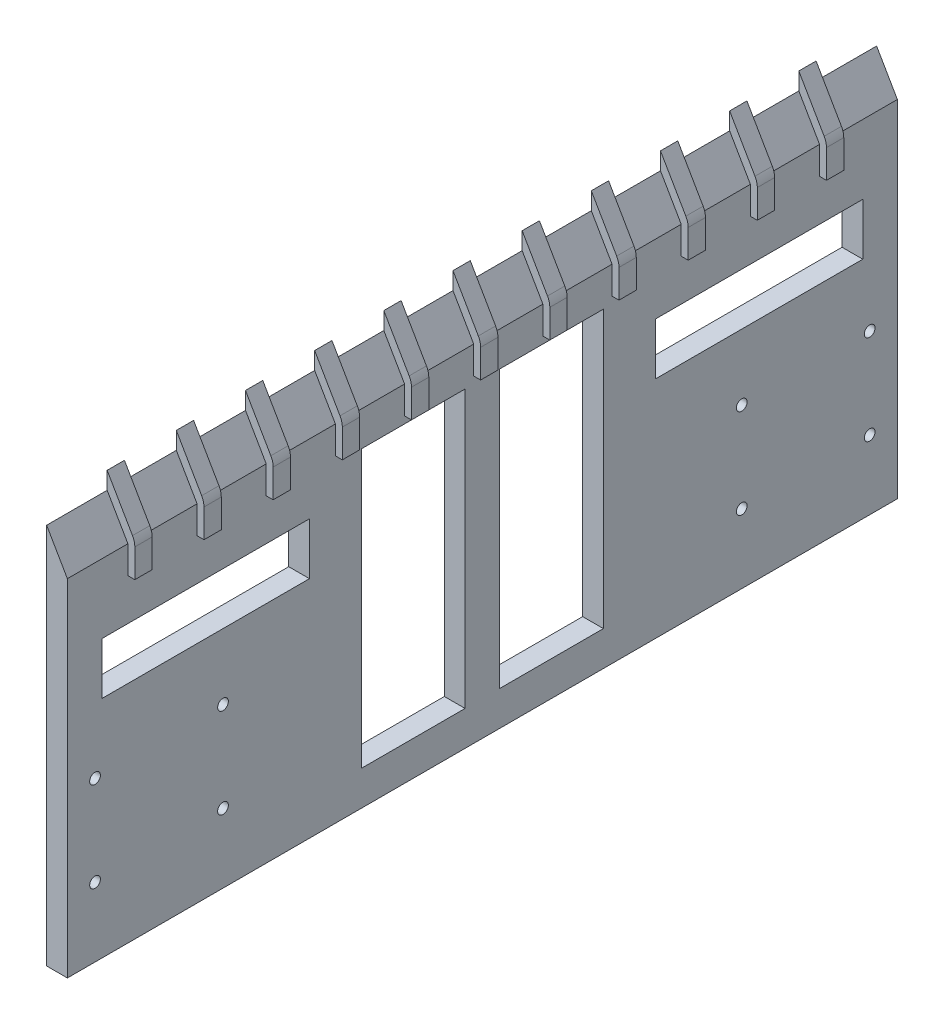
SolidWorks part; units mm, degrees
ref_plane "前视基准面" through (0, 0, 0) normal (0, 0, 1) x (1, 0, 0)
ref_plane "上视基准面" through (0, 0, 0) normal (0, 1, 0) x (1, 0, 0)
ref_plane "右视基准面" through (0, 0, 0) normal (1, 0, 0) x (0, 0, -1)
sketch "草图1" plane through (0, 0, 0) normal (1, 0, 0) x (0, 0, -1)
  line L1 (0, 0) -> (240, 0)
  line L2 (0, 0) -> (0, -100)
  line L3 (0, -100) -> (240, -100)
  line L4 (240, 0) -> (240, -100)
  dimension "D1" = 240
  dimension "D2" = 100
extrude "凸台-拉伸1" add sketch "草图1" along normal blind 6
sketch "草图2" plane through (6, 0, 0) normal (1, 0, 0) x (0, 0, -1)
  line L0 (0, 0) -> (0, -100) construction
  line L1 (8, -54) -> (45, -54) construction
  line L2 (8, -54) -> (8, -80) construction
  line L3 (8, -80) -> (45, -80) construction
  line L4 (45, -54) -> (45, -80) construction
  line L5 (240, 0) -> (0, 0) construction
  line L6 (120, 0) -> (120, -100) construction
  line L7 (0, -100) -> (240, -100) construction
  line L8 (195, -54) -> (195, -80) construction
  line L9 (232, -80) -> (195, -80) construction
  line L10 (232, -54) -> (232, -80) construction
  line L11 (232, -54) -> (195, -54) construction
  circle A0 centre (8, -54) radius 1.55
  circle A1 centre (45, -80) radius 1.55
  circle A2 centre (45, -54) radius 1.55
  circle A3 centre (8, -80) radius 1.55
  circle A4 centre (232, -80) radius 1.55
  circle A5 centre (195, -54) radius 1.55
  circle A6 centre (195, -80) radius 1.55
  circle A7 centre (232, -54) radius 1.55
  dimension "D5" = 3.1
  dimension "D1" = 8
  dimension "D2" = 54
  dimension "D3" = 37
  dimension "D4" = 26
extrude "切除-拉伸1" cut sketch "草图2" against normal through all
sketch "草图3" plane through (6, 0, 0) normal (1, 0, 0) x (0, 0, -1)
  line L0 (120, 0) -> (120, -100) construction
  line L1 (10, -20) -> (70, -20)
  line L2 (10, -20) -> (10, -35)
  line L3 (10, -35) -> (70, -35)
  line L4 (70, -20) -> (70, -35)
  line L5 (240, 0) -> (0, 0) construction
  line L6 (0, -100) -> (240, -100) construction
  line L7 (0, 0) -> (0, -100) construction
  line L8 (170, -20) -> (170, -35)
  line L9 (230, -35) -> (170, -35)
  line L10 (230, -20) -> (230, -35)
  line L11 (230, -20) -> (170, -20)
  dimension "D1" = 10
  dimension "D2" = 20
  dimension "D3" = 15
  dimension "D4" = 60
extrude "切除-拉伸2" cut sketch "草图3" against normal through all
sketch "草图4" plane through (6, 0, 0) normal (1, 0, 0) x (0, 0, -1)
  line L0 (120, 0) -> (120, -100) construction
  line L1 (85, -10) -> (115, -10)
  line L2 (85, -10) -> (85, -90)
  line L3 (85, -90) -> (115, -90)
  line L4 (115, -10) -> (115, -90)
  line L5 (240, 0) -> (0, 0) construction
  line L6 (0, -100) -> (240, -100) construction
  line L7 (0, 0) -> (0, -100) construction
  line L8 (125, -10) -> (125, -90)
  line L9 (155, -90) -> (125, -90)
  line L10 (155, -10) -> (155, -90)
  line L11 (155, -10) -> (125, -10)
  dimension "D1" = 10
  dimension "D2" = 10
  dimension "D3" = 85
  dimension "D4" = 30
extrude "切除-拉伸3" cut sketch "草图4" against normal through all contours L4 L1 L2 L3 | L8 L9 L10 L11
sketch "草图5" plane through (0, 0, 0) normal (-1, 0, 0) x (0, 0, 1)
  circle A0 centre (-195, -80) radius 3
  circle A1 centre (-232, -80) radius 3
  circle A2 centre (-195, -54) radius 3
  circle A3 centre (-232, -54) radius 3
  circle A4 centre (-45, -80) radius 3
  circle A5 centre (-8, -80) radius 3
  circle A6 centre (-8, -54) radius 3
  circle A7 centre (-45, -54) radius 3
  dimension "D1" = 6
extrude "切除-拉伸4" cut sketch "草图5" against normal blind 3
sketch "草图6" plane through (0, 0, 0) normal (0, 0, 1) x (1, 0, 0)
  line L0 (6, 0) -> (0, 0)
  line L1 (0, 0) -> (0, 10.3923)
  line L2 (0, 10.3923) -> (6, 0)
  dimension "D1" = 30
extrude "凸台-拉伸2" add sketch "草图6" against normal blind 240
ref_plane "基准面1" through (0, 0, -117.5) normal (0, 0, 1) x (1, 0, 0)
sketch "草图7" plane through (0, 0, -117.5) normal (0, 0, 1) x (1, 0, 0)
  line L0 (0, 10.3923) -> (0, 15.3923)
  line L1 (0, 15.3923) -> (8, 1.5359)
  line L2 (8, 1.5359) -> (8, -8)
  line L3 (8, -8) -> (6, -8)
  line L4 (6, 0) -> (6, -100) construction
  line L5 (6, -8) -> (6, 0)
  line L6 (6, 0) -> (0, 10.3923)
  point P4 (0, 12.8923)
  dimension "D1" = 5
  dimension "D2" = 2
  dimension "D3" = 8
extrude "凸台-拉伸3" add sketch "草图7" against normal blind 5
pattern_linear "阵列(线性)5" count 6 spacing 20 along (0, 0, 1) count 6 spacing 20 along (0, 0, -1) of "凸台-拉伸3"
fillet "圆角5" radius 5 11 edges at (8, 1.5359, -20) (8, 1.5359, -40) (8, 1.5359, -60) (8, 1.5359, -80) (8, 1.5359, -100) (8, 1.5359, -120) (8, 1.5359, -140) (8, 1.5359, -160) (8, 1.5359, -180) (8, 1.5359, -200) (8, 1.5359, -220)
